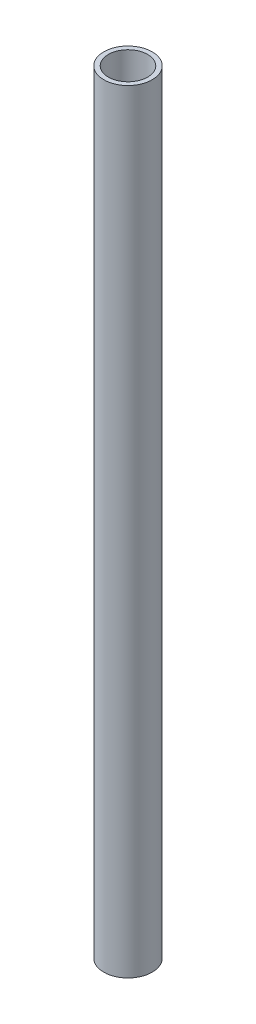
SolidWorks part; units mm, degrees
material "СТ3КП"
ref_plane "Спереди" through (0, 0, 0) normal (0, 0, 1) x (1, 0, 0)
ref_plane "Сверху" through (0, 0, 0) normal (0, 1, 0) x (1, 0, 0)
ref_plane "Справа" through (0, 0, 0) normal (1, 0, 0) x (0, 0, -1)
sketch "Эскиз1" plane through (0, 0, 0) normal (0, 1, 0) x (1, 0, 0)
  line L0 (0, 200889.2922) -> (0, -249032.8193) construction
  line L1 (-130, 9.15) -> (130, 9.15) construction
  circle B0 centre (0, -1.5) radius 8.65
  circle B1 centre (0, -1.5) radius 10.65
sketch_block_instance "Труба 21_3х2 1_2-1"
sketch_block "Труба 21_3х2 1_2" parameters "D2"=21.3, "D1"=2
extrude "Бобышка-Вытянуть1" add sketch "Эскиз1" along normal up to vertex (340 mm away)
